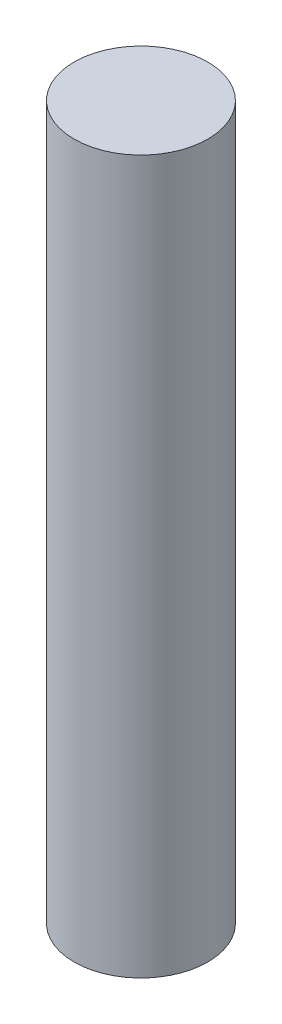
SolidWorks part; units mm, degrees
ref_plane "Front Plane" through (0, 0, 0) normal (0, 0, 1) x (1, 0, 0)
ref_plane "Top Plane" through (0, 0, 0) normal (0, 1, 0) x (1, 0, 0)
ref_plane "Right Plane" through (0, 0, 0) normal (1, 0, 0) x (0, 0, -1)
sketch "Sketch2" plane through (0, 0, 0) normal (0, 1, 0) x (1, 0, 0)
  circle A0 centre (0, 0) radius 1.875
  dimension "D1" = 3.75
extrude "Boss-Extrude1" add sketch "Sketch2" along normal blind 20
